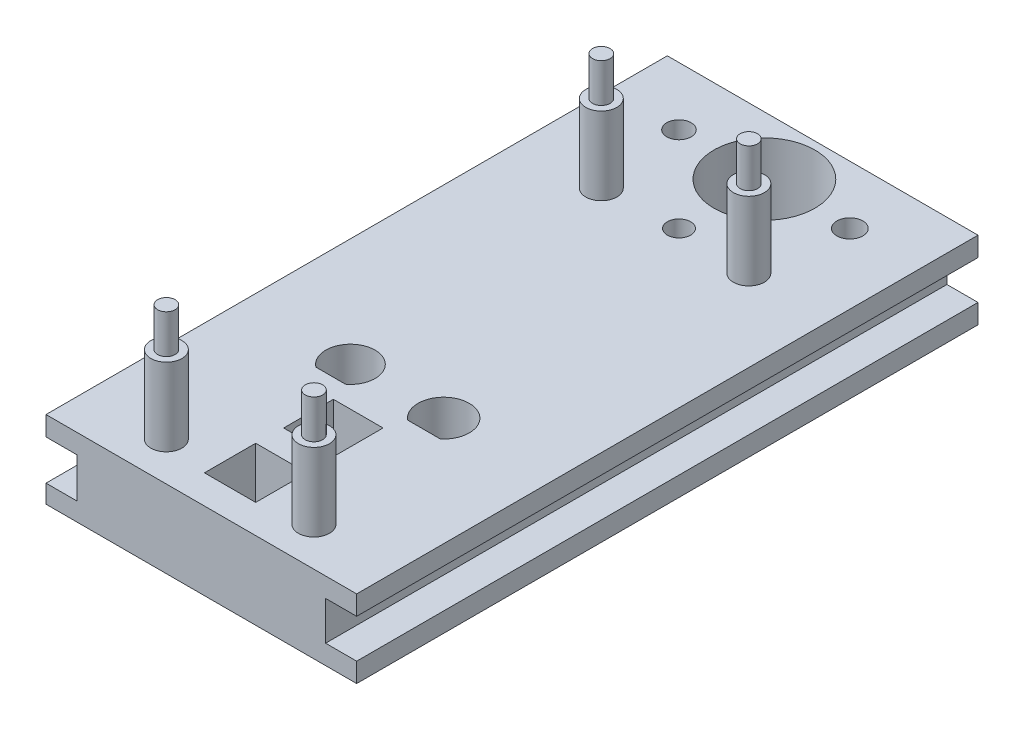
SolidWorks part; units mm, degrees
ref_plane "Plan de face" through (0, 0, 0) normal (0, 0, 1) x (1, 0, 0)
ref_plane "Plan de dessus" through (0, 0, 0) normal (0, 1, 0) x (1, 0, 0)
ref_plane "Plan de droite" through (0, 0, 0) normal (1, 0, 0) x (0, 0, -1)
sketch "Esquisse2" plane through (0, 0, 0) normal (0, 1, 0) x (1, 0, 0)
  line L1 (-20, 40) -> (20, 40)
  line L2 (-20, 40) -> (-20, -40)
  line L3 (-20, -40) -> (20, -40)
  line L4 (20, 40) -> (20, -40)
  line L5 (-20, 40) -> (20, -40) construction
  line L6 (-20, -40) -> (20, 40) construction
  point P0 (0, 0)
  dimension "D1" = 80
  dimension "D2" = 40
extrude "Boss.-Extru.1" add sketch "Esquisse2" along normal blind 10
sketch "Esquisse3" plane through (0, 10, 0) normal (0, 1, 0) x (1, 0, 0)
  line L2 (-20, -40) -> (20, -40) construction
  circle A0 centre (9.5, -35) radius 2
  circle A1 centre (9.5, 21) radius 2
  circle A2 centre (-9.5, -35) radius 2
  circle A3 centre (-9.5, 21) radius 2
  point P2 (0, 0)
  dimension "D3" = 4
  dimension "D5" = 4
  dimension "D7" = 4
  dimension "D8" = 4
  dimension "D1" = 9.5
  dimension "D2" = 5
  dimension "D4" = 56
  dimension "D6" = 19
extrude "Boss.-Extru.2" add sketch "Esquisse3" along normal blind 10
sketch "Esquisse4" plane through (0, 20, 0) normal (0, 1, 0) x (1, 0, 0)
  circle A0 centre (-9.5, -35) radius 1.125
  circle A1 centre (-9.5, -35) radius 2 construction
  circle A2 centre (9.5, -35) radius 1.125
  circle A3 centre (9.5, -35) radius 2 construction
  circle A4 centre (-9.5, 21) radius 1.125
  circle A5 centre (-9.5, 21) radius 2 construction
  circle A6 centre (9.5, 21) radius 1.125
  circle A7 centre (9.5, 21) radius 2 construction
  dimension "D2" = 2.25
  dimension "D3" = 2.25
  dimension "D4" = 2.25
  dimension "D5" = 2.25
  dimension "D1" = 0
extrude "Boss.-Extru.3" add sketch "Esquisse4" along normal blind 5
sketch "Esquisse5" plane through (0, 10, 0) normal (0, 1, 0) x (1, 0, 0)
  line L0 (20, 40) -> (-20, 40) construction
  circle A0 centre (0, 21.5) radius 1.5
  circle A1 centre (-11, 32.5) radius 1.575
  circle A2 centre (11, 32.5) radius 1.675
  circle A3 centre (0, 32.5) radius 6.5
  dimension "D1" = 3
  dimension "D2" = 3.15
  dimension "D3" = 3.35
  dimension "D4" = 13
  dimension "D5" = 7.5
  dimension "D6" = 11
  dimension "D7" = 11
  dimension "D8" = 11
extrude "Enlèv. mat.-Extru.1" cut sketch "Esquisse5" against normal up to next
sketch "Esquisse6" plane through (0, 10, 0) normal (0, 1, 0) x (1, 0, 0)
  line L0 (-20, -40) -> (20, -40) construction
  line L1 (3.3, -36.3) -> (-3.3, -36.3)
  line L2 (3.3, -36.3) -> (3.3, -29.7)
  line L3 (3.3, -29.7) -> (-3.3, -29.7)
  line L4 (-3.3, -36.3) -> (-3.3, -29.7)
  line L5 (3.3, -36.3) -> (-3.3, -29.7) construction
  line L6 (3.3, -29.7) -> (-3.3, -36.3) construction
  line L8 (-3.2, -19.8) -> (3.2, -19.8)
  line L9 (-3.2, -19.8) -> (-3.2, -26.2)
  line L10 (-3.2, -26.2) -> (3.2, -26.2)
  line L11 (3.2, -19.8) -> (3.2, -26.2)
  line L12 (-3.2, -19.8) -> (3.2, -26.2) construction
  line L13 (-3.2, -26.2) -> (3.2, -19.8) construction
  point P0 (0, -33)
  point P8 (0, -23)
  dimension "D1" = 6.6
  dimension "D2" = 7
  dimension "D3" = 6.4
  dimension "D4" = 10
extrude "Enlèv. mat.-Extru.2" cut sketch "Esquisse6" against normal up to next
sketch "Esquisse7" plane through (0, 10, 0) normal (0, 1, 0) x (1, 0, 0)
  line L0 (-7.905, -17.34) -> (-4.095, -17.34)
  line L1 (3.2, -19.8) -> (-3.2, -19.8) construction
  line L2 (3.8901, -17.34) -> (8.1099, -17.34)
  arc A0 (-7.905, -17.34) -> (-4.095, -17.34) centre (-6, -14.8) cw
  arc A1 (3.8901, -17.34) -> (8.1099, -17.34) centre (6, -14.8) cw
  point P0 (0, 0)
  point P2 (-6, -11.625)
  point P5 (0, 0)
  point P10 (6, -11.498)
  dimension "D1" = 3.175
  dimension "D5" = 3.302
  dimension "D2" = 5.715
  dimension "D3" = 5
  dimension "D4" = 6
  dimension "D6" = 5.842
  dimension "D7" = 5
  dimension "D8" = 6
extrude "Enlèv. mat.-Extru.3" cut sketch "Esquisse7" against normal blind 10
sketch "Esquisse8" plane through (0, 0, 40) normal (0, 0, 1) x (1, 0, 0)
  line L0 (20, 10) -> (20, 0) construction
  line L1 (20, 7.5) -> (16, 7.5)
  line L2 (20, 7.5) -> (20, 2.5)
  line L3 (20, 2.5) -> (16, 2.5)
  line L4 (16, 7.5) -> (16, 2.5)
  line L5 (20, 7.5) -> (16, 2.5) construction
  line L6 (20, 2.5) -> (16, 7.5) construction
  line L7 (-20, 10) -> (20, 10) construction
  line L8 (-20, 10) -> (-20, 0) construction
  line L9 (-20, 7.5) -> (-16, 7.5)
  line L10 (-20, 7.5) -> (-20, 2.35)
  line L11 (-20, 2.35) -> (-16, 2.35)
  line L12 (-16, 7.5) -> (-16, 2.35)
  line L13 (-20, 7.5) -> (-16, 2.35) construction
  line L14 (-20, 2.35) -> (-16, 7.5) construction
  point P4 (18, 5)
  point P13 (-18, 4.925)
  dimension "D1" = 2.5
  dimension "D2" = 5
  dimension "D3" = 4
  dimension "D4" = 4
  dimension "D5" = 2.5
  dimension "D6" = 5.15
extrude "Enlèv. mat.-Extru.4" cut sketch "Esquisse8" against normal up to next
